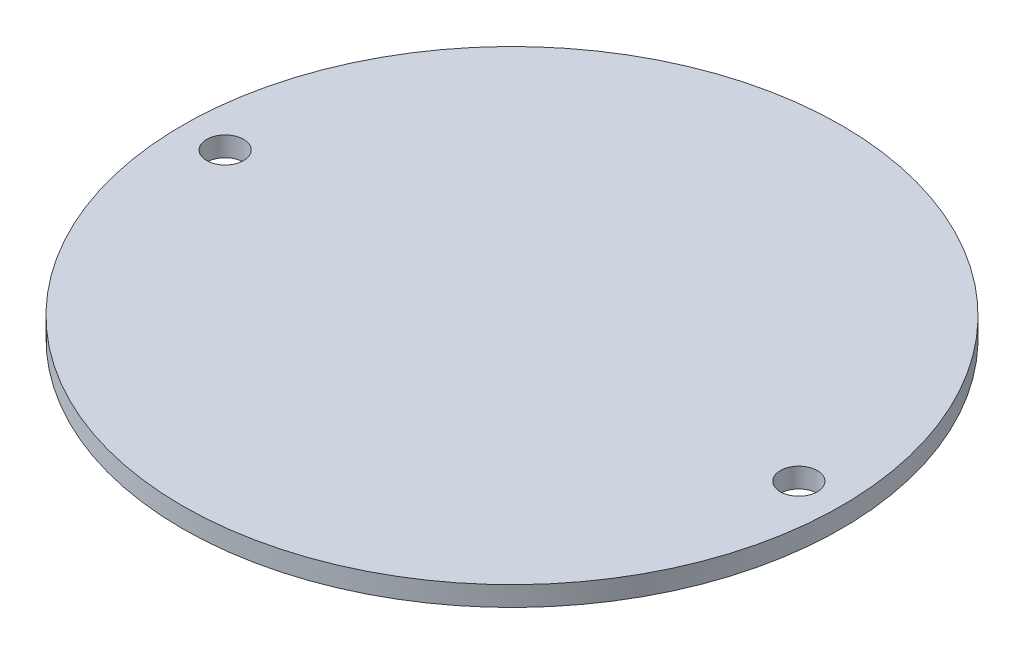
SolidWorks part; units mm, degrees
ref_plane "Front Plane" through (0, 0, 0) normal (0, 0, 1) x (1, 0, 0)
ref_plane "Top Plane" through (0, 0, 0) normal (0, 1, 0) x (1, 0, 0)
ref_plane "Right Plane" through (0, 0, 0) normal (1, 0, 0) x (0, 0, -1)
sketch "Sketch1" plane through (0, 0, 0) normal (0, 1, 0) x (1, 0, 0)
  circle A0 centre (0, 0) radius 62.5
  dimension "D1" = 125
extrude "Boss-Extrude1" add sketch "Sketch1" along normal blind 3.75
hole_wizard "M6 Clearance Hole1" positions "Sketch2" profile "Sketch4" hole size "M6" standard "ANSI Metric" end condition through all
sketch "Sketch2" plane through (0, 3.75, 0) normal (0, 1, 0) x (1, 0, 0)
  line L0 (0, 0) -> (0, 29.5662) construction
  circle A0 centre (0, 0) radius 62.5 construction
  point P7 (-54.4, 0)
  point P39 (0, 0)
  point P40 (0, 0)
  point P41 (0, 0)
  point P42 (0, 0)
  dimension "D1" = 108.8
sketch "Sketch4" plane through (-54.4, 3.75, 0) normal (1, 0, 0) x (0, 0, 1)
  line L0 (0, 0) -> (0, 3.75)
  line L1 (0, 3.75) -> (3.5, 3.75)
  line L2 (3.5, 3.75) -> (3.5, 0)
  line L5 (3.5, 0) -> (0, 0)
  line L11 (0, -6.35) -> (0, 107.95) construction
  dimension "Thru Hole Dia." = 7
  dimension "Thru Hole Depth" = 3.75
pattern_circular "CirPattern1" count 2 over 360 about axis through (0, 0, 0) along (0, 1, 0) of "M6 Clearance Hole1"
